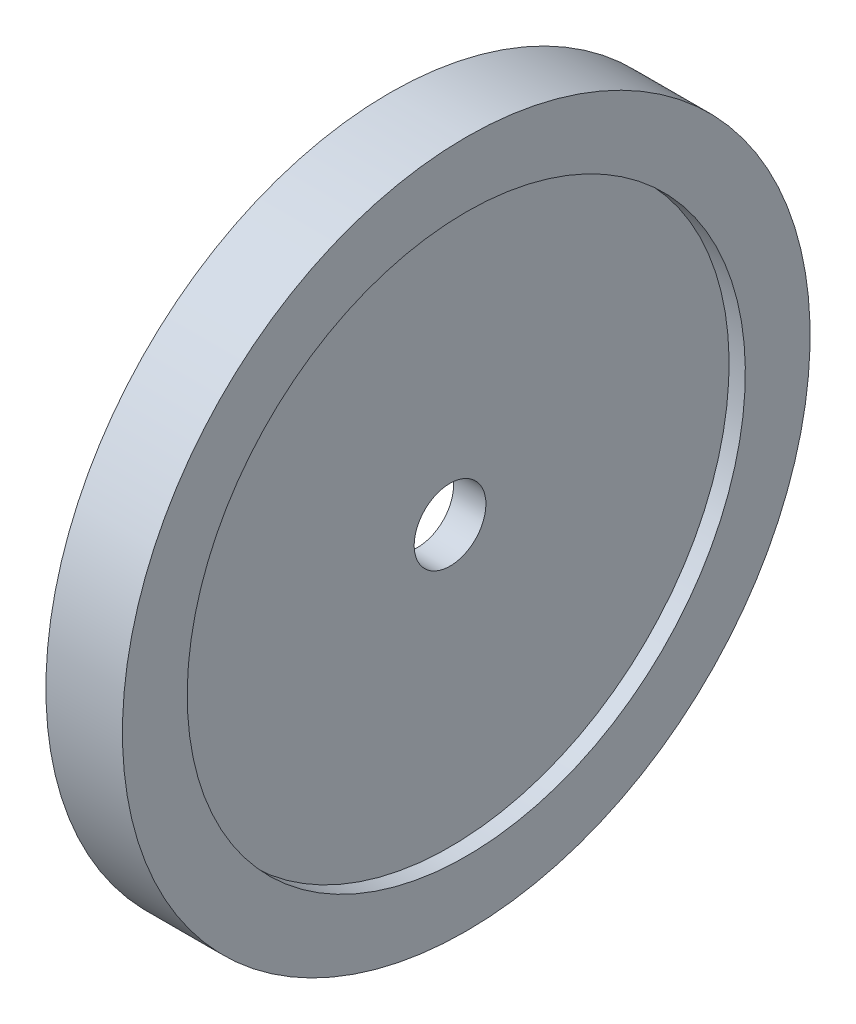
SolidWorks part; units mm, degrees
ref_plane "Front Plane" through (0, 0, 0) normal (0, 0, 1) x (1, 0, 0)
ref_plane "Top Plane" through (0, 0, 0) normal (0, 1, 0) x (1, 0, 0)
ref_plane "Right Plane" through (0, 0, 0) normal (1, 0, 0) x (0, 0, -1)
sketch "Sketch1" plane through (0, 0, 0) normal (0, 0, 1) x (1, 0, 0)
  line L0 (0, 0) -> (0, 28)
  line L1 (0, 28) -> (-2.8, 28)
  line L2 (-2.8, 28) -> (-2.8, 34.5)
  line L3 (-2.8, 34.5) -> (4.88, 34.5)
  line L4 (4.88, 34.5) -> (4.88, 28)
  line L5 (4.88, 28) -> (3.25, 28)
  line L6 (3.25, 28) -> (3.25, 0)
  line L7 (3.25, 0) -> (0, 0)
  dimension "D1" = 6.5
  dimension "D2" = 6.5
  dimension "D3" = 7.68
  dimension "D4" = 2.8
  dimension "D5" = 1.63
  dimension "D6" = 34.5
revolve "Revolve1" add sketch "Sketch1" angle 360 about L7
sketch "Sketch2" plane through (0, 0, 0) normal (-1, 0, 0) x (0, 0, 1)
  circle A0 centre (0, 0) radius 17.5
  circle A1 centre (0, 0) radius 11.5
  dimension "D1" = 23
  dimension "D2" = 35
extrude "Boss-Extrude1" add sketch "Sketch2" along normal blind 1.5
sketch "Sketch4" plane through (0, 0, 0) normal (1, 0, 0) x (0, 0, -1)
  circle A0 centre (0, 0) radius 3.6
  dimension "D1" = 7.2
extrude "Cut-Extrude2" cut sketch "Sketch4" along normal through all
